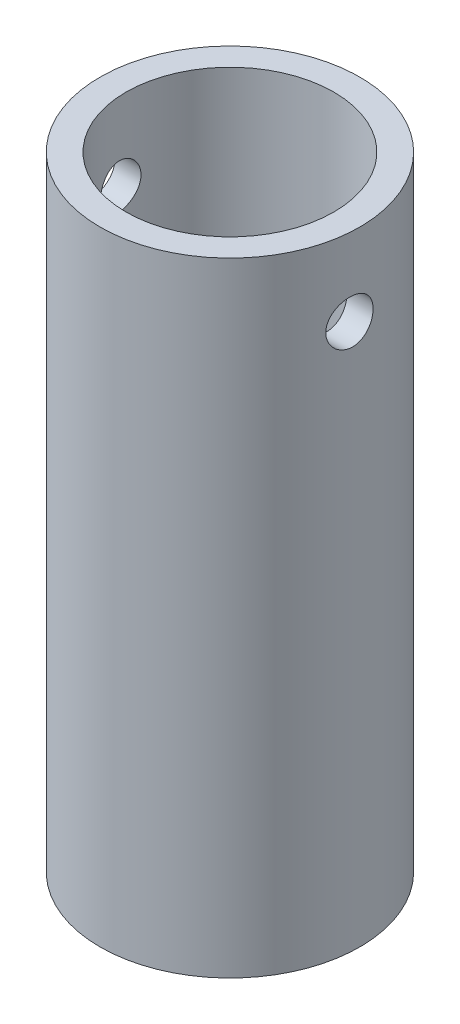
SolidWorks part; units mm, degrees
ref_plane "Front Plane" through (0, 0, 0) normal (0, 0, 1) x (1, 0, 0)
ref_plane "Top Plane" through (0, 0, 0) normal (0, 1, 0) x (1, 0, 0)
ref_plane "Right Plane" through (0, 0, 0) normal (1, 0, 0) x (0, 0, -1)
sketch "Sketch2" plane through (0, 0, 0) normal (0, 1, 0) x (1, 0, 0)
  circle A0 centre (0, 0) radius 7.9375
  dimension "D1" = 15.875
extrude "Pistone Base" add sketch "Sketch2" along normal blind 38.1
sketch "Sketch3" plane through (0, 38.1, 0) normal (0, 1, 0) x (1, 0, 0)
  circle A0 centre (0, 0) radius 6.35
  point P3 (-12.4081, 4.7187)
  dimension "D1" = 12.7
extrude "Drill Hole 1" cut sketch "Sketch3" against normal blind 19.05
sketch "Sketch6" plane through (0, 0, 0) normal (1, 0, 0) x (0, 0, -1)
  line L0 (-7.9375, 0) -> (7.9375, 0) construction
  circle A0 centre (-0.5021, 33.3248) radius 1.3589
  point P4 (0, 0)
  dimension "D1" = 2.7178
  dimension "D2" = 33.3248
extrude "Top Whole" cut sketch "Sketch6" against normal through all both and the other way through all
